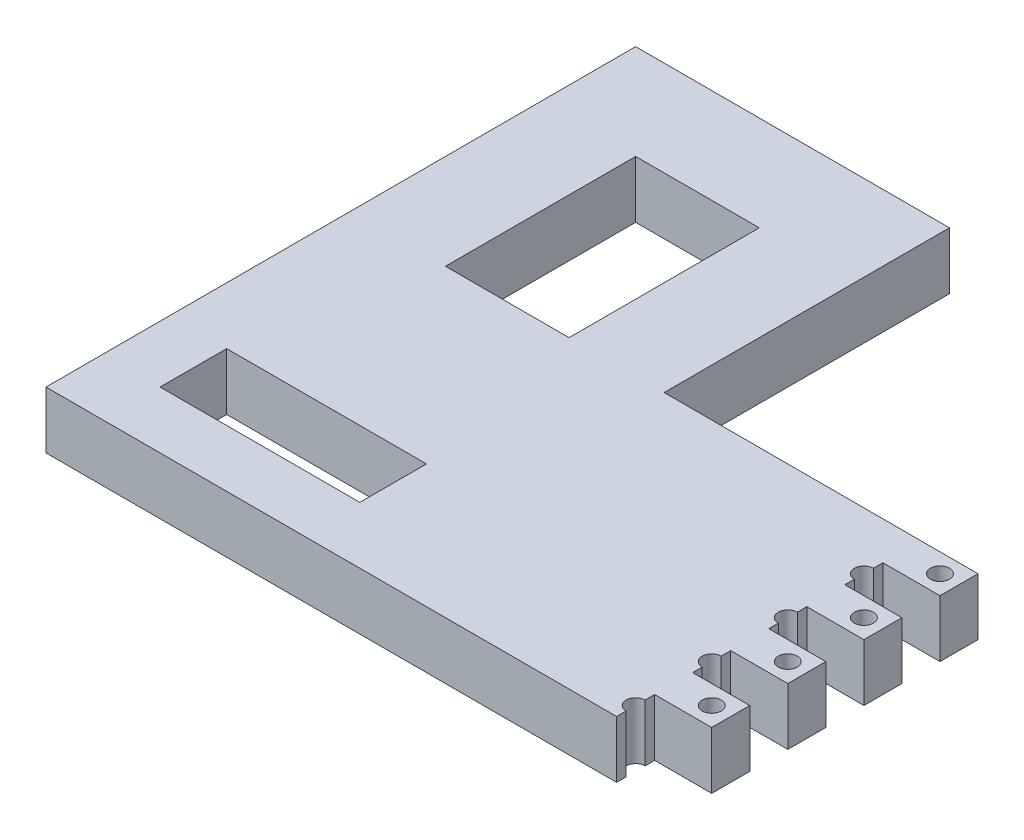
SolidWorks part; units mm, degrees
ref_plane "Front Plane" through (0, 0, 0) normal (0, 0, 1) x (1, 0, 0)
ref_plane "Top Plane" through (0, 0, 0) normal (0, 1, 0) x (1, 0, 0)
ref_plane "Right Plane" through (0, 0, 0) normal (1, 0, 0) x (0, 0, -1)
sketch "Sketch1" plane through (0, 0, 0) normal (0, 1, 0) x (1, 0, 0)
  line L2 (33, 32) -> (66, 32)
  line L3 (66, 20) -> (66, 24)
  line L4 (66, 24) -> (60, 24)
  line L5 (60, 24) -> (60, 28)
  line L6 (60, 28) -> (66, 28)
  line L7 (66, 28) -> (66, 32)
  line L8 (60, 16) -> (66, 16)
  line L9 (66, 16) -> (66, 12)
  line L10 (66, 12) -> (60, 12)
  line L11 (60, 8) -> (60, 12)
  line L12 (66, 20) -> (60, 20)
  line L13 (60, 20) -> (60, 16)
  line L14 (60, 0) -> (0, 0)
  line L15 (0, 0) -> (0, 20)
  line L16 (60, 8) -> (66, 8)
  line L17 (66, 8) -> (66, 4)
  line L18 (66, 4) -> (60, 4)
  line L19 (60, 4) -> (60, 0)
  line L20 (0, 20) -> (0, 62)
  line L21 (0, 62) -> (33, 62)
  line L22 (33, 62) -> (33, 32)
  dimension "D1" = 4
  dimension "D2" = 60
  dimension "D3" = 4
  dimension "D4" = 6
  dimension "D5" = 4
  dimension "D6" = 4
  dimension "D8" = 30
  dimension "D9" = 4
  dimension "D10" = 4
  dimension "D11" = 4
  dimension "D12" = 4
  dimension "D14" = 33
extrude "Boss-Extrude1" add sketch "Sketch1" along normal blind 6
sketch "Sketch2" plane through (0, 6, 0) normal (0, 1, 0) x (1, 0, 0)
  line L1 (6, 13) -> (27, 13)
  line L2 (6, 13) -> (6, 6)
  line L3 (6, 6) -> (27, 6)
  line L4 (27, 13) -> (27, 6)
  line L5 (0, 0) -> (60, 0) construction
  line L6 (0, 62) -> (0, 0) construction
  line L7 (66, 32) -> (33, 32) construction
  line L8 (10, 52) -> (23, 52)
  line L9 (10, 52) -> (10, 32)
  line L10 (10, 32) -> (23, 32)
  line L11 (23, 52) -> (23, 32)
  dimension "D1" = 7
  dimension "D2" = 21
  dimension "D3" = 6
  dimension "D4" = 6
  dimension "D5" = 20
  dimension "D6" = 13
  dimension "D7" = 10
extrude "Cut-Extrude1" cut sketch "Sketch2" against normal through all
sketch "Sketch3" plane through (0, 6, 0) normal (0, 1, 0) x (1, 0, 0)
  line L0 (66, 28) -> (66, 32) construction
  line L1 (66, 20) -> (66, 24) construction
  line L2 (66, 12) -> (66, 16) construction
  line L3 (66, 4) -> (66, 8) construction
  line L4 (60, 24) -> (60, 28) construction
  line L5 (60, 16) -> (60, 20) construction
  line L6 (60, 8) -> (60, 12) construction
  line L7 (60, 0) -> (60, 4) construction
  circle A0 centre (64, 30) radius 1
  circle A1 centre (64, 22) radius 1
  circle A2 centre (64, 14) radius 1
  circle A3 centre (64, 6) radius 1
  circle A4 centre (60, 26) radius 1
  circle A5 centre (60, 18) radius 1
  circle A6 centre (60, 10) radius 1
  circle A7 centre (60, 2) radius 1
  point P4 (66, 30)
  point P13 (66, 22)
  point P16 (66, 14)
  point P19 (66, 6)
  dimension "D1" = 2
  dimension "D2" = 2
extrude "Cut-Extrude2" cut sketch "Sketch3" against normal through all
